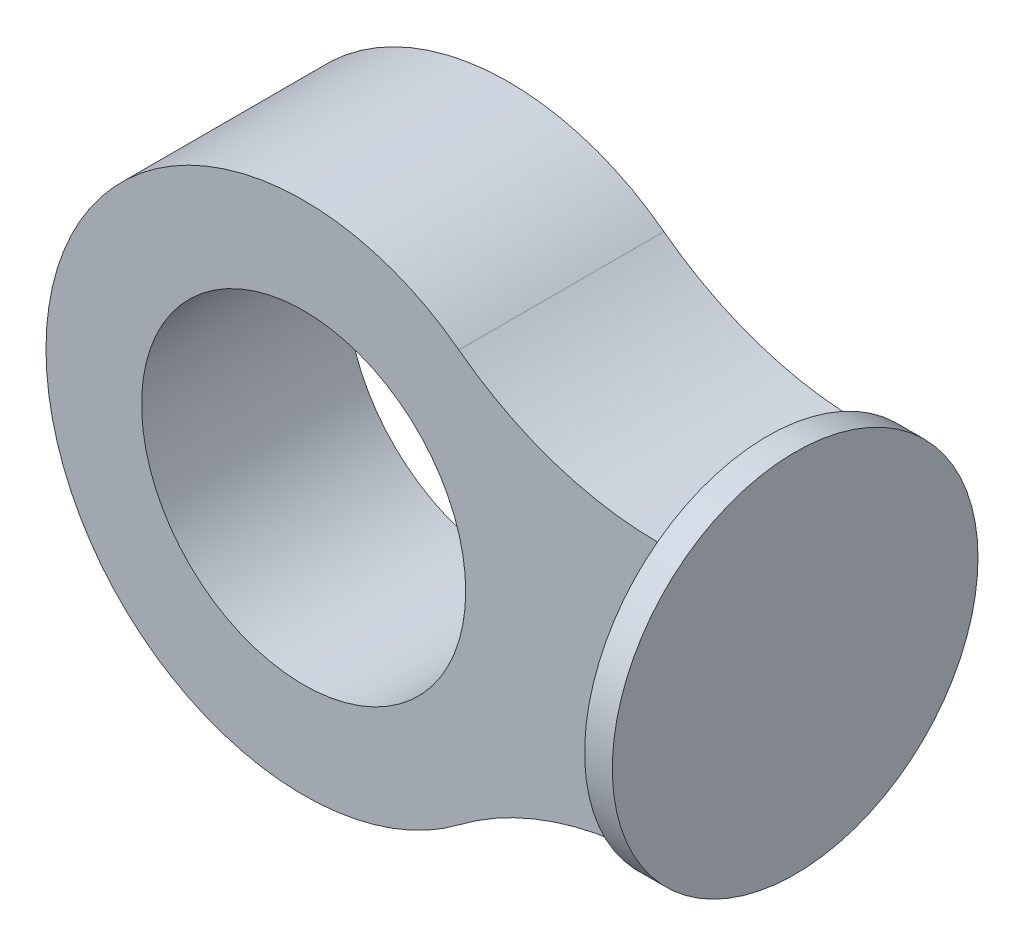
SolidWorks part; units mm, degrees
ref_plane "Front Plane" through (0, 0, 0) normal (0, 0, 1) x (1, 0, 0)
ref_plane "Top Plane" through (0, 0, 0) normal (0, 1, 0) x (1, 0, 0)
ref_plane "Right Plane" through (0, 0, 0) normal (1, 0, 0) x (0, 0, -1)
sketch "Sketch1" plane through (0, 0, 0) normal (0, 0, 1) x (1, 0, 0)
  line L0 (0, 0) -> (46.5, 0) construction
  line L1 (64.1658, 25) -> (65.2078, 25)
  line L3 (64.1658, -25) -> (65.2078, -25)
  line L4 (65.2078, 25) -> (65.2078, -25)
  line L5 (65.2078, 0) -> (73.8615, 0) construction
  arc A0 (28.0161, 37.1127) -> (28.0161, -37.1127) centre (0, 0) ccw
  circle A1 centre (0, 0) radius 29.25
  arc A2 (64.1658, -25) -> (28.0161, -37.1127) centre (64.1658, -85) ccw
  arc A3 (64.1658, 25) -> (28.0161, 37.1127) centre (64.1658, 85) cw
  point P8 (65.2078, 0)
  point P15 (39.2078, 25)
  dimension "D1" = 26
  dimension "D3" = 93
  dimension "D4" = 58.5
  dimension "D5" = 60
  dimension "D2" = 50
extrude "Boss-Extrude1" add sketch "Sketch1" along normal blind 37
sketch "Sketch2" plane through (65.2078, 0, 0) normal (1, 0, 0) x (0, 0, -1)
  line L0 (-37, -25) -> (-37, 25) construction
  line L1 (-37, 25) -> (0, 25) construction
  circle A0 centre (-18.5, 0) radius 33
  dimension "D1" = 18.5
  dimension "D2" = 25
extrude "Boss-Extrude2" add sketch "Sketch2" along normal blind 5
